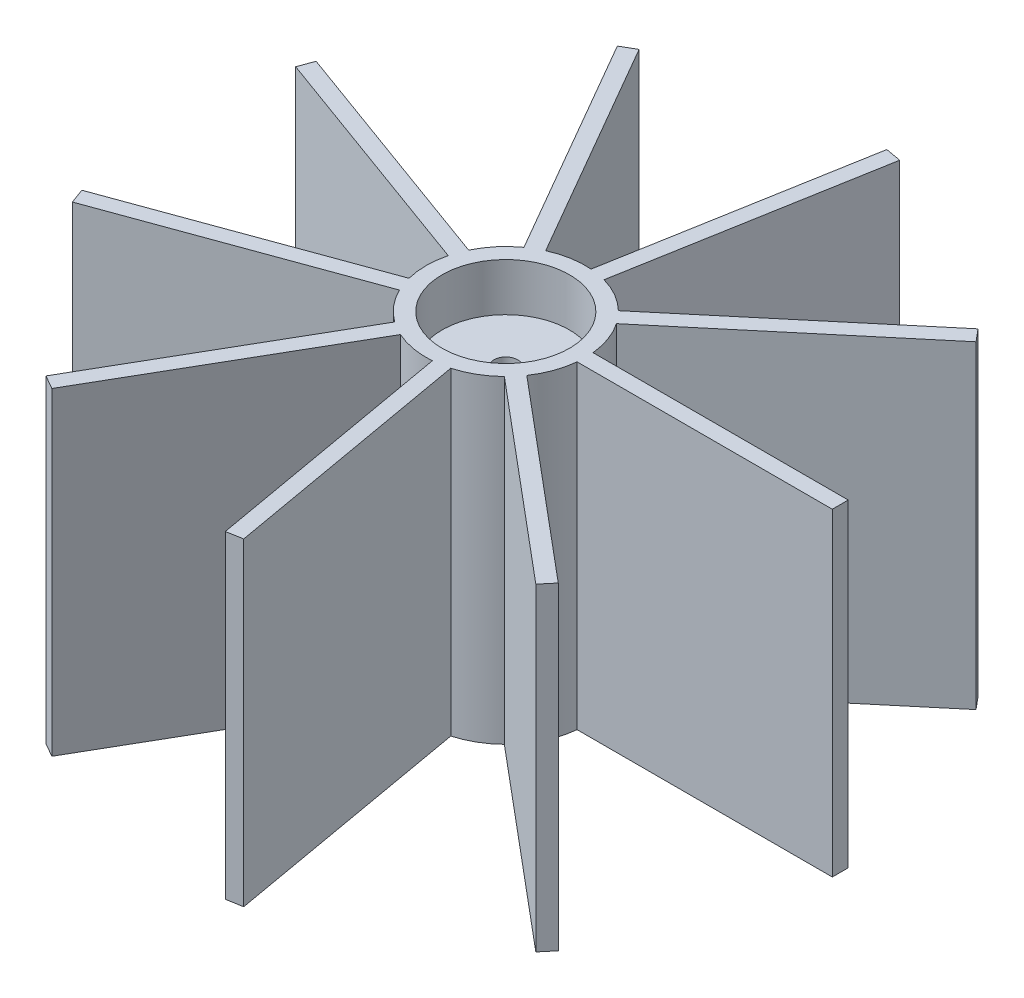
SolidWorks part; units mm, degrees
ref_plane "Front Plane" through (0, 0, 0) normal (0, 0, 1) x (1, 0, 0)
ref_plane "Top Plane" through (0, 0, 0) normal (0, 1, 0) x (1, 0, 0)
ref_plane "Right Plane" through (0, 0, 0) normal (1, 0, 0) x (0, 0, -1)
sketch "Sketch1" plane through (0, 0, 0) normal (0, 1, 0) x (1, 0, 0)
  circle A0 centre (0, 0) radius 5
  circle A1 centre (0, 0) radius 3
  dimension "D1" = 6
  dimension "D2" = 10
extrude "Boss-Extrude2" add sketch "Sketch1" along normal mid plane 35
sketch "Sketch4" plane through (0, 17.5, 0) normal (0, 1, 0) x (1, 0, 0)
  line L0 (3, 0) -> (21, 0)
  circle A0 centre (0, 0) radius 3 construction
  dimension "D1" = 18
extrude "Extrude-Thin1" add sketch "Sketch4" against normal blind 35 thin thin type mid plane wall 1
pattern_circular "CirPattern1" count 9 over 360 about axis through (0, 0, 0) along (0, 1, 0) of "Extrude-Thin1"
ref_plane "Plane1" through (0, -17.5, 0) normal (0, -1, 0) x (-1, 0, 0)
sketch "Sketch5" plane through (0, -17.5, 0) normal (0, -1, 0) x (-1, 0, 0)
  circle A0 centre (0, 0) radius 3
extrude "Boss-Extrude3" add sketch "Sketch5" against normal blind 15
sketch "Sketch6" plane through (0, -17.5, 0) normal (0, -1, 0) x (-1, 0, 0)
  circle A0 centre (0, 0) radius 3.5
  circle A1 centre (0, 0) radius 5
  circle A2 centre (0, 0) radius 1.5
  dimension "D1" = 1.5
  dimension "D2" = 10
  dimension "D3" = 2
extrude "Cut-Extrude1" cut sketch "Sketch6" against normal blind 6 contours A0 A2
sketch "Sketch15" plane through (0, -17.5, 0) normal (0, -1, 0) x (1, 0, 0)
  circle A0 centre (0, 0) radius 1.5
extrude "Cut-Extrude2" cut sketch "Sketch15" against normal blind 2
sketch "Sketch17" plane through (0, -17.5, 0) normal (0, -1, 0) x (1, 0, 0)
  line L0 (21, -0.5) -> (21, 0.5) construction
  circle A0 centre (18.5, 0) radius 2.5
  dimension "D1" = 5
  dimension "D2" = 2.5
extrude "Boss-Extrude4" add sketch "Sketch17" against normal blind 3
sketch "Sketch18" plane through (0, -17.5, 0) normal (0, -1, 0) x (1, 0, 0)
  circle A0 centre (18.5, 0) radius 2
  dimension "D1" = 4
extrude "Cut-Extrude3" cut sketch "Sketch18" against normal blind 2
sketch "Sketch19" plane through (0, 17.5, 0) normal (0, 1, 0) x (1, 0, 0)
  circle A0 centre (0, 0) radius 4
  circle A1 centre (0, 0) radius 3 construction
  dimension "D1" = 1
extrude "Cut-Extrude4" cut sketch "Sketch19" against normal up to surface (20 mm away) up to face at (0, -2.5, -3)
sketch "Sketch20" plane through (0, -17.5, 0) normal (0, -1, 0) x (-1, 0, 0)
  line L1 (22.8386, 22.8623) -> (-22.8386, 22.8623)
  line L2 (22.8386, 22.8623) -> (22.8386, -22.8623)
  line L3 (22.8386, -22.8623) -> (-22.8386, -22.8623)
  line L4 (-22.8386, 22.8623) -> (-22.8386, -22.8623)
  line L5 (22.8386, 22.8623) -> (-22.8386, -22.8623) construction
  line L6 (22.8386, -22.8623) -> (-22.8386, 22.8623) construction
  point P0 (0, 0)
extrude "Cut-Extrude5" cut sketch "Sketch20" against normal blind 8
sketch "Sketch21" plane through (0, -9.5, 0) normal (0, -1, 0) x (1, 0, 0)
  circle A0 centre (0, 0) radius 3
  dimension "D1" = 6
extrude "Boss-Extrude5" add sketch "Sketch21" along normal blind 1
sketch "Sketch22" plane through (0, 0, 0) normal (0, 0, 1) x (1, 0, 0)
  line L0 (0, 0) -> (0, -37.0893) construction
sketch "Sketch23" plane through (0, 0, 0) normal (1, 0, 0) x (0, 0, -1)
  line L0 (-8.7928, -17.5) -> (7.1377, -17.5) construction
  line L1 (-13.1155, -9.5) -> (-2.8148, -9.5) construction
  line L2 (-55, -17.5) -> (55, -17.5) construction
  line L3 (-3, -10.5) -> (-2, -10.5)
  line L4 (-3, -10.5) -> (3, -10.5) construction
  line L5 (-9.9121, -17.5) -> (-8.9121, -17.5)
  line L6 (0, -11.1307) -> (0, -16.3839) construction
  line L7 (0, 0) -> (0, -37.0893) construction
  line L8 (-8.9121, -17.5) -> (0, -17.5)
  line L9 (0, -17.5) -> (0, -10.5)
  line L10 (0, -10.5) -> (-2, -10.5)
  arc A0 (-3, -10.5) -> (-9.9121, -17.5) centre (0.7568, -21.1223) ccw
  dimension "D1" = 8
  dimension "D2" = 1
  dimension "D3" = 1
revolve "Revolve1" add sketch "Sketch23" angle 360 about L6
sketch "Sketch24" plane through (0, -17.5, 0) normal (0, -1, 0) x (1, 0, 0)
  circle A2 centre (0, 0) radius 9.9121
  circle A3 centre (0, 0) radius 9.9121
  dimension "D1" = 0
extrude "Boss-Extrude6" add sketch "Sketch24" along normal blind 0.5
sketch "Sketch25" plane through (0, -18, 0) normal (0, -1, 0) x (1, 0, 0)
  line L0 (-1.1163, 9.8491) -> (1.1163, -9.8491) construction
  circle A0 centre (0, 0) radius 9.9121 construction
  circle A1 centre (-0.5667, 5) radius 3.2
  point P6 (0, 0)
  dimension "D1" = 6.4
  dimension "D2" = 5
extrude "Cut-Extrude6" cut sketch "Sketch25" against normal blind 2.1
sketch "Sketch26" plane through (0, -18, 0) normal (0, -1, 0) x (1, 0, 0)
  circle A0 centre (-0.5667, 5) radius 3.2
extrude "Boss-Extrude7" add sketch "Sketch26" against normal blind 0.25
sketch "Sketch27" plane through (0, -18, 0) normal (0, -1, 0) x (1, 0, 0)
  line L0 (0, 9.9121) -> (0, -9.9121) construction
  line L1 (-9.9121, 0) -> (9.9121, 0) construction
  arc A1 (-7.6138, 6.3467) -> (-7.6138, -6.3467) centre (-9.9121, 0) cw
  circle A2 centre (0, 0) radius 9.9121 construction
  arc A3 (7.6138, 6.3467) -> (7.6138, -6.3467) centre (9.9121, 0) ccw
  arc A4 (7.6138, 6.3467) -> (7.6138, -6.3467) centre (0, 0) cw
  arc A5 (-7.6138, 6.3467) -> (-7.6138, -6.3467) centre (0, 0) ccw
  arc A6 (-7.6138, 6.3467) -> (0, 9.9121) centre (0, 0) cw
  arc A7 (7.6138, 6.3467) -> (0, 9.9121) centre (0, 0) ccw
  arc A8 (7.6138, -6.3467) -> (0, -9.9121) centre (0, 0) cw
  arc A9 (-7.6138, -6.3467) -> (0, -9.9121) centre (0, 0) ccw
  spline S0 degree 3 poles (-5.3686, 4.9919) (-4.9981, 7.5397) (-2.6164, 9.8379) (0, 9.9121) knots 0 0 0 0 1 1 1 1
  spline S1 degree 3 poles (5.3686, 4.9919) (4.9981, 7.5397) (2.6164, 9.8379) (0, 9.9121) knots 0 0 0 0 1 1 1 1
  spline S2 degree 3 poles (5.3686, -4.9919) (4.9981, -7.5397) (2.6164, -9.8379) (0, -9.9121) knots 0 0 0 0 1 1 1 1
  spline S3 degree 3 poles (-5.3686, -4.9919) (-4.9981, -7.5397) (-2.6164, -9.8379) (0, -9.9121) knots 0 0 0 0 1 1 1 1
  circle M1 centre (0, 0) radius 9.9121
extrude "Cut-Extrude8" cut sketch "Sketch27" against normal blind 7.5 contours A1 M1 | A3 M1 | S3 A1 M1 | A3 S2 M1 | A1 S0 M1 | S1 A3 M1
sketch "Sketch28" plane through (0, -18, 0) normal (0, -1, 0) x (1, 0, 0)
  circle A0 centre (0, 0) radius 0.5
  dimension "D1" = 1
extrude "Cut-Extrude9" cut sketch "Sketch28" against normal blind 1.5
sketch "Sketch29" plane through (0, 17.5, 0) normal (0, 1, 0) x (1, 0, 0)
  line L108 (3.4896, -3.5809) -> (15.7655, -13.8816)
  line L109 (15.7655, -13.8816) -> (16.4083, -13.1155)
  line L110 (16.4083, -13.1155) -> (4.1324, -2.8148)
  line L111 (4.9749, -0.5) -> (21, -0.5)
  line L112 (21, -0.5) -> (21, 0.5)
  line L113 (21, 0.5) -> (4.9749, 0.5)
  line L114 (4.1324, 2.8148) -> (16.4083, 13.1155)
  line L115 (16.4083, 13.1155) -> (15.7655, 13.8816)
  line L116 (15.7655, 13.8816) -> (3.4896, 3.5809)
  line L117 (1.3563, 4.8125) -> (4.139, 20.5941)
  line L118 (4.139, 20.5941) -> (3.1542, 20.7678)
  line L119 (3.1542, 20.7678) -> (0.3715, 4.9862)
  line L120 (-2.0545, 4.5584) -> (-10.067, 18.4365)
  line L121 (-10.067, 18.4365) -> (-10.933, 17.9365)
  line L122 (-10.933, 17.9365) -> (-2.9205, 4.0584)
  line L123 (-4.5039, 2.1714) -> (-19.5625, 7.6523)
  line L124 (-19.5625, 7.6523) -> (-19.9046, 6.7126)
  line L125 (-19.9046, 6.7126) -> (-4.8459, 1.2317)
  line L126 (-4.8459, -1.2317) -> (-19.9046, -6.7126)
  line L127 (-19.9046, -6.7126) -> (-19.5625, -7.6523)
  line L128 (-19.5625, -7.6523) -> (-4.5039, -2.1714)
  line L129 (-2.9205, -4.0584) -> (-10.933, -17.9365)
  line L130 (-10.933, -17.9365) -> (-10.067, -18.4365)
  line L131 (-10.067, -18.4365) -> (-2.0545, -4.5584)
  line L132 (0.3715, -4.9862) -> (3.1542, -20.7678)
  line L133 (3.1542, -20.7678) -> (4.139, -20.5941)
  line L134 (4.139, -20.5941) -> (1.3563, -4.8125)
  line L135 (3.4896, -3.5809) -> (15.7655, -13.8816)
  line L136 (15.7655, -13.8816) -> (16.4083, -13.1155)
  line L137 (16.4083, -13.1155) -> (4.1324, -2.8148)
  line L138 (4.9749, -0.5) -> (21, -0.5)
  line L139 (21, -0.5) -> (21, 0.5)
  line L140 (21, 0.5) -> (4.9749, 0.5)
  line L141 (4.1324, 2.8148) -> (16.4083, 13.1155)
  line L142 (16.4083, 13.1155) -> (15.7655, 13.8816)
  line L143 (15.7655, 13.8816) -> (3.4896, 3.5809)
  line L144 (1.3563, 4.8125) -> (4.139, 20.5941)
  line L145 (4.139, 20.5941) -> (3.1542, 20.7678)
  line L146 (3.1542, 20.7678) -> (0.3715, 4.9862)
  line L147 (-2.0545, 4.5584) -> (-10.067, 18.4365)
  line L148 (-10.067, 18.4365) -> (-10.933, 17.9365)
  line L149 (-10.933, 17.9365) -> (-2.9205, 4.0584)
  line L150 (-4.5039, 2.1714) -> (-19.5625, 7.6523)
  line L151 (-19.5625, 7.6523) -> (-19.9046, 6.7126)
  line L152 (-19.9046, 6.7126) -> (-4.8459, 1.2317)
  line L153 (-4.8459, -1.2317) -> (-19.9046, -6.7126)
  line L154 (-19.9046, -6.7126) -> (-19.5625, -7.6523)
  line L155 (-19.5625, -7.6523) -> (-4.5039, -2.1714)
  line L156 (-2.9205, -4.0584) -> (-10.933, -17.9365)
  line L157 (-10.933, -17.9365) -> (-10.067, -18.4365)
  line L158 (-10.067, -18.4365) -> (-2.0545, -4.5584)
  line L159 (0.3715, -4.9862) -> (3.1542, -20.7678)
  line L160 (3.1542, -20.7678) -> (4.139, -20.5941)
  line L161 (4.139, -20.5941) -> (1.3563, -4.8125)
  arc A36 (1.3563, -4.8125) -> (3.4896, -3.5809) centre (0, 0) ccw
  arc A37 (4.1324, -2.8148) -> (4.9749, -0.5) centre (0, 0) ccw
  arc A38 (4.9749, 0.5) -> (4.1324, 2.8148) centre (0, 0) ccw
  arc A39 (3.4896, 3.5809) -> (1.3563, 4.8125) centre (0, 0) ccw
  arc A40 (0.3715, 4.9862) -> (-2.0545, 4.5584) centre (0, 0) ccw
  arc A41 (-2.9205, 4.0584) -> (-4.5039, 2.1714) centre (0, 0) ccw
  arc A42 (-4.8459, 1.2317) -> (-4.8459, -1.2317) centre (0, 0) ccw
  arc A43 (-4.5039, -2.1714) -> (-2.9205, -4.0584) centre (0, 0) ccw
  arc A44 (-2.0545, -4.5584) -> (0.3715, -4.9862) centre (0, 0) ccw
  arc A45 (1.3563, -4.8125) -> (3.4896, -3.5809) centre (0, 0) ccw
  arc A46 (4.1324, -2.8148) -> (4.9749, -0.5) centre (0, 0) ccw
  arc A47 (4.9749, 0.5) -> (4.1324, 2.8148) centre (0, 0) ccw
  arc A48 (3.4896, 3.5809) -> (1.3563, 4.8125) centre (0, 0) ccw
  arc A49 (0.3715, 4.9862) -> (-2.0545, 4.5584) centre (0, 0) ccw
  arc A50 (-2.9205, 4.0584) -> (-4.5039, 2.1714) centre (0, 0) ccw
  arc A51 (-4.8459, 1.2317) -> (-4.8459, -1.2317) centre (0, 0) ccw
  arc A52 (-4.5039, -2.1714) -> (-2.9205, -4.0584) centre (0, 0) ccw
  arc A53 (-2.0545, -4.5584) -> (0.3715, -4.9862) centre (0, 0) ccw
  dimension "D1" = 0
extrude "Cut-Extrude10" cut sketch "Sketch29" against normal blind 7
sketch "Sketch30" plane through (0, -2.5, 0) normal (0, 1, 0) x (1, 0, 0)
  circle A1 centre (0, 0) radius 4
  circle A2 centre (0, 0) radius 4
  dimension "D1" = 0
extrude "Boss-Extrude8" add sketch "Sketch30" along normal blind 10
sketch "Sketch33" plane through (0, -9.5, 0) normal (0, -1, 0) x (1, 0, 0)
  circle A0 centre (0, 0) radius 18.0649
extrude "Cut-Extrude13" cut sketch "Sketch33" along normal blind 20
sketch "Sketch34" plane through (0, -9.5, 0) normal (0, -1, 0) x (1, 0, 0)
  circle A0 centre (0, 0) radius 3
  dimension "D1" = 6
extrude "Cut-Extrude14" cut sketch "Sketch34" against normal blind 8.5
sketch "Sketch35" plane through (0, 7.5, 0) normal (0, 1, 0) x (1, 0, 0)
  circle A0 centre (0, 0) radius 0.75
  dimension "D1" = 1.5
extrude "Cut-Extrude16" cut sketch "Sketch35" against normal blind 3
equation "\"NumFlaps\"=9"
equation "\"D1@CirPattern1\"=\"NumFlaps\""
equation "\"FlapHeight\"=35"
equation "\"D1@Extrude-Thin1\"=\"FlapHeight\""
equation "\"FanBaseHeight\"=35"
equation "\"D1@Boss-Extrude2\"=\"FanBaseHeight\""
equation "\"FanExtrude\"=6"
equation "\"D1@Sketch1\"=\"FanExtrude\""
equation "\"magnet_diameter\"= 6.4"
equation "\"magnet_length\"= 2.1"
equation "\"magnet_distance\"= 5"
equation "\"D1@Sketch25\"=\"magnet_diameter\""
equation "\"D2@Sketch25\"=\"magnet_distance\""
equation "\"D1@Cut-Extrude6\"=\"magnet_length\""
equation "\"CutglobeArc\"=6.75"
equation "\"FanExtraExtrude\"=7"
equation "\"D1@Cut-Extrude10\"=\"FanExtraExtrude\""
